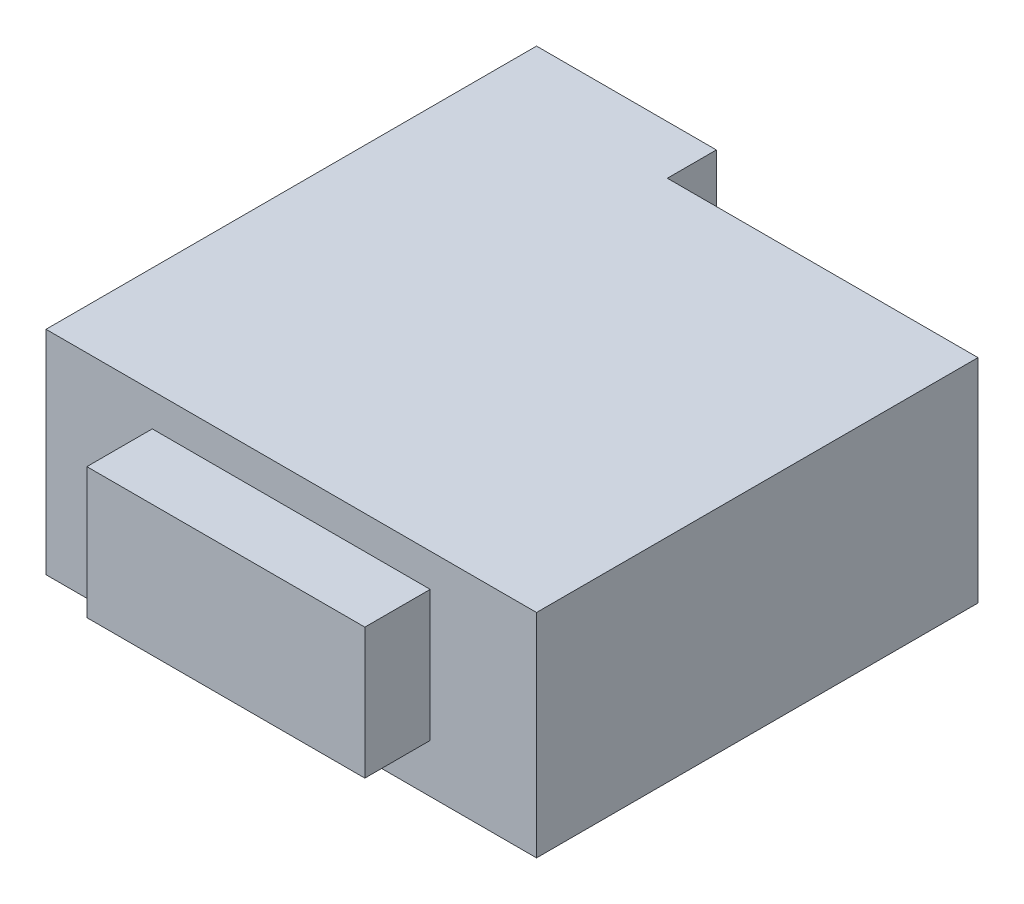
SolidWorks part; units mm, degrees
ref_plane "Front Plane" through (0, 0, 0) normal (0, 0, 1) x (1, 0, 0)
ref_plane "Top Plane" through (0, 0, 0) normal (0, 1, 0) x (1, 0, 0)
ref_plane "Right Plane" through (0, 0, 0) normal (1, 0, 0) x (0, 0, -1)
sketch "Sketch1" plane through (0, 0, 0) normal (0, 1, 0) x (1, 0, 0)
  line L1 (-150, -135) -> (150, -135)
  line L2 (-150, -135) -> (-150, 135)
  line L3 (-150, 135) -> (150, 135)
  line L4 (150, -135) -> (150, 135)
  line L5 (-150, -135) -> (150, 135) construction
  line L6 (-150, 135) -> (150, -135) construction
  point P0 (0, 0)
  dimension "D1" = 300
  dimension "D2" = 270
extrude "Boss-Extrude1" add sketch "Sketch1" along normal blind 130
sketch "Sketch2" plane through (0, 0, -135) normal (0, 0, -1) x (-1, 0, 0)
  line L0 (-150, 130) -> (150, 130) construction
  line L1 (150, 0) -> (40, 0)
  line L2 (150, 0) -> (150, 130)
  line L3 (150, 130) -> (40, 130)
  line L4 (40, 0) -> (40, 130)
  dimension "D1" = 110
extrude "Boss-Extrude2" add sketch "Sketch2" along normal blind 30
sketch "Sketch3" plane through (0, 0, 135) normal (0, 0, 1) x (1, 0, 0)
  line L1 (-85, 29.7512) -> (85, 29.7512)
  line L2 (-85, 29.7512) -> (-85, 109.7512)
  line L3 (-85, 109.7512) -> (85, 109.7512)
  line L4 (85, 29.7512) -> (85, 109.7512)
  line L8 (0, 130) -> (0, 0) construction
  line L9 (-150, 130) -> (150, 130) construction
  point P4 (0, 109.7512)
  dimension "D1" = 0
  dimension "D2" = 80
  dimension "D3" = 170
extrude "Boss-Extrude3" add sketch "Sketch3" along normal blind 40
